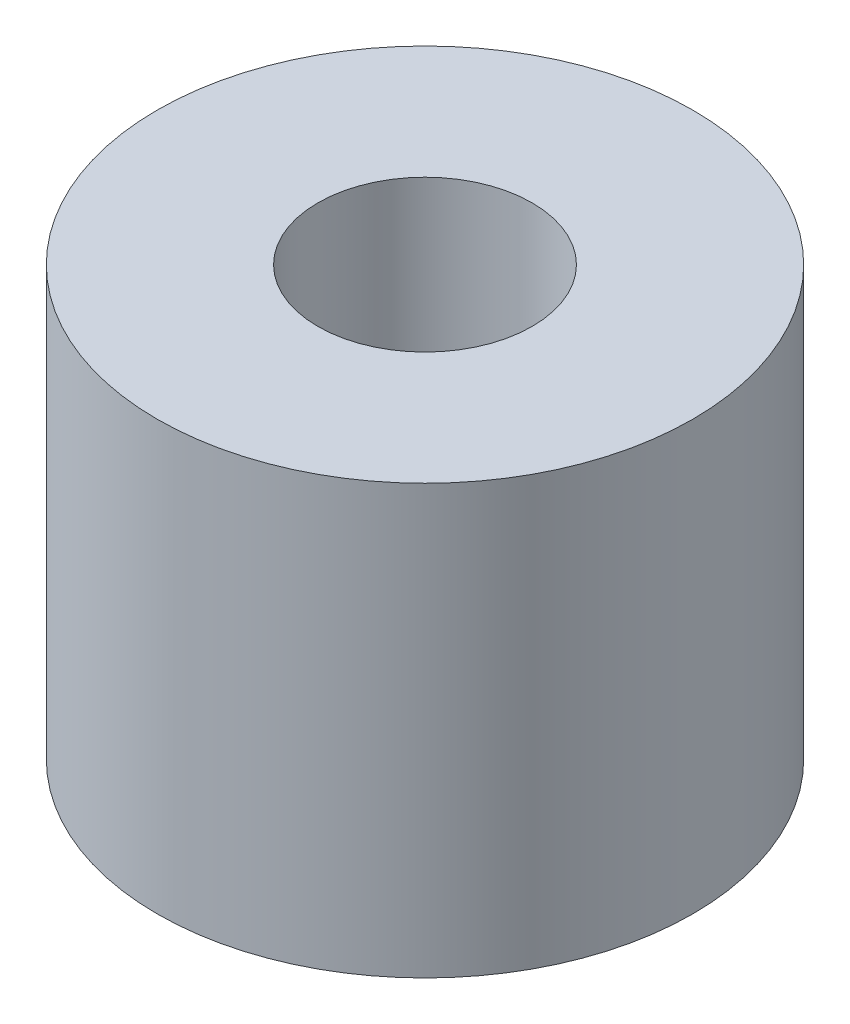
SolidWorks part; units mm, degrees
ref_plane "Front Plane" through (0, 0, 0) normal (0, 0, 1) x (1, 0, 0)
ref_plane "Top Plane" through (0, 0, 0) normal (0, 1, 0) x (1, 0, 0)
ref_plane "Right Plane" through (0, 0, 0) normal (1, 0, 0) x (0, 0, -1)
sketch "Sketch1" plane through (0, 0, 0) normal (0, 1, 0) x (1, 0, 0)
  circle A0 centre (0, 0) radius 4
  circle A1 centre (0, 0) radius 10
  dimension "D1" = 8
  dimension "D2" = 20
extrude "Boss-Extrude1" add sketch "Sketch1" along normal blind 16
